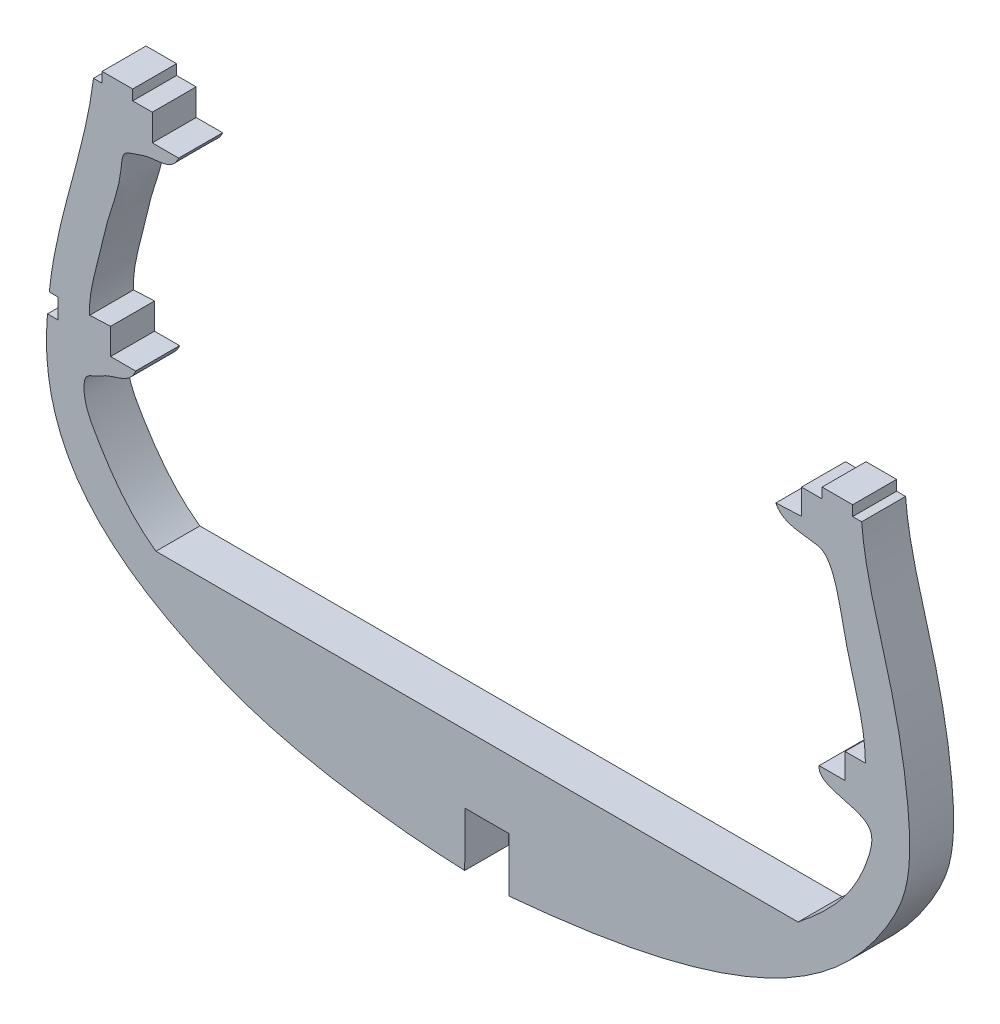
SolidWorks part; units mm, degrees
ref_plane "前视基准面" through (0, 0, 0) normal (0, 0, 1) x (1, 0, 0)
ref_plane "上视基准面" through (0, 0, 0) normal (0, 1, 0) x (1, 0, 0)
ref_plane "右视基准面" through (0, 0, 0) normal (1, 0, 0) x (0, 0, -1)
other "Configuration Table"
sketch "草图1" plane through (0, 0, 0) normal (0, 0, 1) x (1, 0, 0)
  line L0 (556.8633, 460.8086) -> (1980.8143, -29.4971) construction
  line L28 (1355.2433, -740.4528) -> (1238.2918, -740.4528)
  line L31 (1294.5868, -752.8347) -> (1294.5308, -762.6927)
  line L32 (1359.0778, -713.8671) -> (1363.807, -713.8671)
  line L33 (1363.807, -713.8671) -> (1363.807, -709.2657)
  line L34 (1363.807, -709.2657) -> (1367.5136, -709.2657)
  line L35 (1366.8245, -671.5335) -> (1365.189, -671.5335)
  line L36 (1365.189, -671.5335) -> (1365.189, -669.661)
  line L37 (1365.189, -669.661) -> (1359.6188, -669.661)
  line L38 (1359.6188, -669.661) -> (1359.6188, -671.5335)
  line L39 (1359.6188, -671.5335) -> (1355.8737, -671.5335)
  line L40 (1355.8737, -671.5335) -> (1355.8737, -676.1557)
  line L41 (1355.8737, -676.1557) -> (1351.1971, -676.3723)
  line L42 (1218.5361, -712.889) -> (1220.4211, -712.889)
  line L43 (1220.4211, -712.889) -> (1220.4211, -709.2657)
  line L44 (1220.4211, -709.2657) -> (1218.8727, -709.2657)
  line L45 (1242.4344, -676.3723) -> (1237.6248, -676.3723)
  line L46 (1237.6248, -676.3723) -> (1237.6248, -671.5335)
  line L47 (1237.6248, -671.5335) -> (1234.0581, -671.5335)
  line L48 (1234.0581, -671.5335) -> (1234.0581, -669.661)
  line L49 (1234.0581, -669.661) -> (1228.492, -669.661)
  line L50 (1228.492, -669.661) -> (1228.492, -671.5335)
  line L51 (1228.492, -671.5335) -> (1226.9248, -671.5335)
  line L52 (1234.5985, -713.8671) -> (1230.0401, -713.8671)
  line L53 (1230.0401, -713.8671) -> (1230.0401, -709.0959)
  line L54 (1230.0401, -709.0959) -> (1226.2223, -709.2657)
  line L55 (1302.589, -752.8347) -> (1302.589, -762.6927)
  line L56 (1294.5868, -752.8347) -> (1302.589, -752.8347)
  spline S9 degree 3 poles (1355.2433, -740.4528) (1360.9184, -735.8863) (1366.5635, -730.4611) (1370.0375, -716.2375) (1358.7476, -717.2757) (1359.0778, -713.8671) knots 0 0 0 0 0.579254 0.707642 1 1 1 1
  spline S10 degree 3 poles (1367.5136, -709.2657) (1367.3181, -702.1371) (1364.1999, -696.0872) (1361.7471, -679.6189) (1358.2673, -679.1983) (1355.3603, -678.7927) (1352.1934, -678.5459) (1351.1971, -676.3723) knots 0 0 0 0 0.446994 0.733624 0.768819 0.798951 1 1 1 1
  spline S11 degree 3 poles (1366.8245, -671.5335) (1367.4305, -679.3526) (1372.0746, -692.7883) (1375.6243, -711.1561) (1375.8622, -724.7307) (1370.894, -734.4355) (1360.8556, -747.4773) (1336.6445, -758.7457) (1313.3819, -761.6998) (1302.589, -762.6927) knots 0 0 0 0 0.162516 0.293754 0.39289 0.434798 0.518823 0.731439 0.974989 0.974989 0.974989 0.974989
  spline S12 degree 3 poles (1294.5308, -762.6927) (1282.2393, -762.2107) (1263.2612, -759.9568) (1229.1685, -746.3217) (1216.734, -733.2642) (1218.5361, -712.889) knots 0 0 0 0 0.31706 0.38517 1 1 1 1
  spline S13 degree 3 poles (1226.9248, -671.5335) (1225.3777, -684.3601) (1220.1464, -696.3703) (1218.8727, -709.2657) knots 0 0 0 0 1 1 1 1
  spline S14 degree 3 poles (1226.2223, -709.2657) (1226.0463, -705.6234) (1227.8165, -700.2658) (1229.6, -691.4373) (1231.9509, -686.0394) (1232.0932, -680.3283) (1234.6181, -679.7181) (1237.8846, -678.3643) (1241.2666, -679.1446) (1242.4344, -676.3723) knots 0 0 0 0 0.268047 0.415436 0.662017 0.730188 0.783123 0.832352 1 1 1 1
  spline S15 degree 3 poles (1238.2918, -740.4528) (1233.6899, -737.2129) (1228.9805, -730.7413) (1224.844, -723.0466) (1225.4059, -718.9075) (1227.4633, -718.3816) (1230.2838, -716.4032) (1233.5592, -716.519) (1234.5985, -713.8671) knots 0 0 0 0 0.45939 0.659456 0.710843 0.767464 0.814991 1 1 1 1
  dimension "D3" = 9.858
extrude "凸台-拉伸1" add sketch "草图1" along normal blind 8
